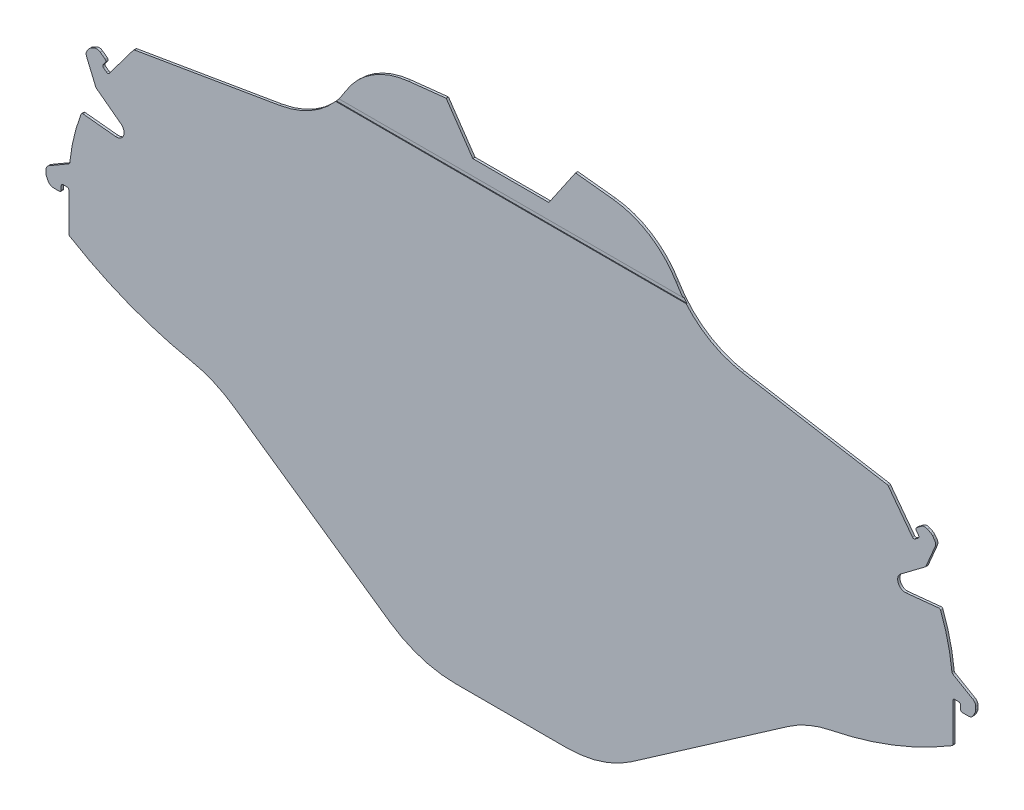
SolidWorks part; units mm, degrees
ref_plane "Front Plane" through (0, 0, 0) normal (0, 0, 1) x (1, 0, 0)
ref_plane "Top Plane" through (0, 0, 0) normal (0, 1, 0) x (1, 0, 0)
ref_plane "Right Plane" through (0, 0, 0) normal (1, 0, 0) x (0, 0, -1)
sketch "Sketch1" plane through (0, 0, 0) normal (0, 0, 1) x (1, 0, 0)
  line L0 (-24, -91.7648) -> (24, -91.7648)
  line L1 (0, 0) -> (0, -91.7648) construction
  line L2 (-10, 0) -> (-17, 10.2352)
  line L5 (-100.1804, -19.9556) -> (-60.7439, -13.2648)
  line L7 (-24, -91.7648) -> (-78.2662, -84.0567)
  line L8 (-17, 10.2352) -> (-26.9419, 9.1584)
  line L13 (-122.5, -58.7648) -> (122.5, -58.7648) construction
  line L14 (-60.7439, -13.2648) -> (-60.7439, -58.7648) construction
  line L15 (-113.5977, -28.7648) -> (-113.5977, -58.7648) construction
  line L16 (-10, 0) -> (10, 0)
  line L17 (10, 0) -> (17, 10.2352)
  line L18 (113.5977, -28.7648) -> (113.5977, -58.7648) construction
  line L19 (60.7439, -13.2648) -> (60.7439, -58.7648) construction
  line L20 (17, 10.2352) -> (26.9419, 9.1584)
  line L21 (24, -91.7648) -> (78.2662, -84.0567)
  line L22 (100.1804, -19.9556) -> (60.7439, -13.2648)
  line L23 (-17, 10.2352) -> (17, 10.2352) construction
  line L24 (0, 10.2352) -> (0, 0) construction
  arc A0 (-26.9419, 9.1584) -> (-43.4614, -1.4344) centre (-24.5729, -12.7137) ccw
  arc A1 (-43.4614, -1.4344) -> (-60.7439, -13.2648) centre (-64.9257, 11.383) cw
  arc A2 (-113.5977, -28.7648) -> (-100.1804, -19.9556) centre (-96.8349, -39.6739) cw
  arc A3 (-122.5, -58.7648) -> (-113.5977, -28.7648) centre (-67.5, -58.7648) cw
  arc A8 (-122.5, -58.7648) -> (-115.7111, -70.7648) centre (-108.5, -58.7648) ccw
  arc A9 (-115.7111, -70.7648) -> (-78.2662, -84.0567) centre (-64.2032, 14.9495) ccw
  arc A10 (115.7111, -70.7648) -> (78.2662, -84.0567) centre (64.2032, 14.9495) cw
  arc A11 (122.5, -58.7648) -> (115.7111, -70.7648) centre (108.5, -58.7648) cw
  arc A12 (122.5, -58.7648) -> (113.5977, -28.7648) centre (67.5, -58.7648) ccw
  arc A13 (113.5977, -28.7648) -> (100.1804, -19.9556) centre (96.8349, -39.6739) ccw
  arc A14 (43.4614, -1.4344) -> (60.7439, -13.2648) centre (64.9257, 11.383) ccw
  arc A15 (26.9419, 9.1584) -> (43.4614, -1.4344) centre (24.5729, -12.7137) cw
  dimension "D5" = 55
  dimension "D7" = 20
  dimension "D9" = 25
  dimension "D11" = 22
  dimension "D12" = 14
  dimension "D19" = 100
  dimension "D2" = 50.7439
  dimension "D3" = 102
  dimension "D4" = 10
  dimension "D6" = 14
  dimension "D8" = 40
  dimension "D10" = 58.7648
  dimension "D13" = 188.084
  dimension "D14" = 12.4
  dimension "D15" = 45.5
  dimension "D16" = 30
  dimension "D17" = 33
  dimension "D18" = 118.187
  dimension "D20" = 20
extrude "Main Shape" add sketch "Sketch1" along normal blind 0.6
sketch "Sketch2" plane through (0, 0, 0.6) normal (0, 0, 1) x (1, 0, 0)
  line L0 (0, 0) -> (0, -91.7648) construction
  line L1 (-24, -91.7648) -> (24, -91.7648) construction
  line L5 (-121.15, -59.7648) -> (-121.15, -57.7648)
  line L15 (-116.15, -59.7648) -> (-116.15, -70.4898)
  line L23 (118.15, -59.7648) -> (121.15, -59.7648) construction
  line L24 (113.6534, -43.3803) -> (119.6776, -41.3722) construction
  line L42 (-60.7439, -13.2648) -> (-100.1804, -19.9556) construction
  line L43 (-99.0635, -19.7662) -> (-100.1804, -19.9556)
  line L45 (-118.15, -59.7648) -> (-118.15, -61.7648)
  line L46 (-118.15, -61.7648) -> (-120.15, -61.7648)
  line L47 (-120.15, -61.7648) -> (-121.15, -59.7648)
  line L48 (-121.15, -57.7648) -> (-115.9855, -54.7675)
  line L49 (-113.6534, -43.3803) -> (-119.6776, -41.3722) construction
  line L50 (-111.02, -27.3748) -> (-108.6868, -32.8713)
  line L71 (-118.15, -59.7648) -> (-116.15, -59.7648)
  line L72 (-118.15, -59.7648) -> (-121.15, -59.7648) construction
  line L73 (-109.82, -25.7748) -> (-111.02, -27.3748)
  line L74 (-107.82, -24.7748) -> (-109.82, -25.7748)
  line L75 (-106.22, -25.9748) -> (-107.82, -24.7748)
  line L76 (-107.42, -27.5748) -> (-106.22, -25.9748)
  line L77 (-107.42, -27.5748) -> (-105.82, -28.7748)
  line L78 (-105.82, -28.7748) -> (-99.0635, -19.7662)
  line L79 (105.82, -28.7748) -> (99.0635, -19.7662)
  line L80 (107.42, -27.5748) -> (105.82, -28.7748)
  line L81 (107.42, -27.5748) -> (106.22, -25.9748)
  line L82 (106.22, -25.9748) -> (107.82, -24.7748)
  line L83 (107.82, -24.7748) -> (109.82, -25.7748)
  line L84 (109.82, -25.7748) -> (111.02, -27.3748)
  line L85 (118.15, -59.7648) -> (116.15, -59.7648)
  line L86 (111.02, -27.3748) -> (108.6868, -32.8713)
  line L87 (121.15, -57.7648) -> (115.9855, -54.7675)
  line L88 (120.15, -61.7648) -> (121.15, -59.7648)
  line L89 (118.15, -61.7648) -> (120.15, -61.7648)
  line L90 (118.15, -59.7648) -> (118.15, -61.7648)
  line L91 (99.0635, -19.7662) -> (100.1804, -19.9556)
  line L92 (116.15, -59.7648) -> (116.15, -70.4898)
  line L93 (121.15, -59.7648) -> (121.15, -57.7648)
  arc A9 (-106.42, -29.5748) -> (-116.15, -58.7648) centre (-67.5, -58.7648) ccw construction
  arc A11 (-113.5977, -28.7648) -> (-122.5, -58.7648) centre (-67.5, -58.7648) ccw construction
  arc A13 (-107.5, -28.7648) -> (-117.5, -58.7648) centre (-67.5, -58.7648) ccw construction
  arc A14 (-105.34, -30.3848) -> (-114.8, -58.7648) centre (-67.5, -58.7648) ccw construction
  arc A15 (-105.34, -30.3848) -> (-107.5, -28.7648) centre (-106.42, -29.5748) ccw construction
  arc A16 (-117.5, -58.7648) -> (-114.8, -58.7648) centre (-116.15, -58.7648) ccw construction
  arc A18 (115.9855, -54.7675) -> (108.6868, -32.8713) centre (67.5, -58.7648) ccw
  arc A19 (122.5, -58.7648) -> (116.15, -70.4898) centre (108.5, -58.7648) cw
  arc A21 (113.5977, -28.7648) -> (122.5, -58.7648) centre (67.5, -58.7648) cw
  arc A22 (100.1804, -19.9556) -> (113.5977, -28.7648) centre (96.8349, -39.6739) cw
  arc A23 (106.42, -29.5748) -> (116.15, -58.7648) centre (67.5, -58.7648) cw construction
  arc A33 (-122.5, -58.7648) -> (-115.7111, -70.7648) centre (-108.5, -58.7648) ccw construction
  arc A34 (-100.1804, -19.9556) -> (-113.5977, -28.7648) centre (-96.8349, -39.6739) ccw construction
  arc A35 (-100.1804, -19.9556) -> (-113.5977, -28.7648) centre (-96.8349, -39.6739) ccw
  arc A36 (-113.5977, -28.7648) -> (-122.5, -58.7648) centre (-67.5, -58.7648) ccw
  arc A37 (-122.5, -58.7648) -> (-116.15, -70.4898) centre (-108.5, -58.7648) ccw
  arc A39 (-115.9855, -54.7675) -> (-108.6868, -32.8713) centre (-67.5, -58.7648) cw
  arc A40 (107.5, -28.7648) -> (117.5, -58.7648) centre (67.5, -58.7648) cw construction
  arc A41 (105.34, -30.3848) -> (114.8, -58.7648) centre (67.5, -58.7648) cw construction
  arc A42 (105.34, -30.3848) -> (107.5, -28.7648) centre (106.42, -29.5748) cw construction
  arc A43 (117.5, -58.7648) -> (114.8, -58.7648) centre (116.15, -58.7648) cw construction
  point P24 (-113.6534, -43.3803)
  point P67 (113.6534, -43.3803)
  dimension "D1" = 1.35
  dimension "D2" = 5
  dimension "D3" = 2
  dimension "D7" = 1
  dimension "D4" = 2
  dimension "D5" = 2
  dimension "D6" = 2
  dimension "D8" = 5
  dimension "D9" = 3
extrude "Tabs" cut sketch "Sketch2" against normal through all both and the other way through all
sketch "Sketch5" plane through (0, 0, 0.6) normal (0, 0, 1) x (1, 0, 0)
  line L0 (-78.2662, -84.0567) -> (-24, -121.7648)
  line L1 (-24, -121.7648) -> (24, -121.7648)
  line L2 (24, -121.7648) -> (78.2662, -84.0567)
  line L3 (-78.2662, -84.0567) -> (-24, -91.7648) construction
  line L4 (24, -91.7648) -> (78.2662, -84.0567) construction
  line L5 (-24, -91.7648) -> (24, -91.7648) construction
  line L6 (24, -91.7648) -> (78.2662, -84.0567)
  line L7 (-24, -91.7648) -> (24, -91.7648)
  line L8 (-78.2662, -84.0567) -> (-24, -91.7648)
  dimension "D1" = 30
extrude "Chin guard" add sketch "Sketch5" against normal up to surface (0.6 mm away) up to face at (0, -39.2508, 0)
fillet "Fillet1" radius 30 4 edges at (-78.2662, -84.0567, 0.3) (78.2662, -84.0567, 0.3) (24, -121.7648, 0.3) (-24, -121.7648, 0.3)
sketch "Sketch8" plane through (0, 0, 0.6) normal (0, 0, 1) x (1, 0, 0)
  line L0 (10, 0) -> (-10, 0) construction
  line L1 (-50, -4) -> (50, -4)
  line L2 (-50, -4) -> (-50, -5)
  line L3 (-50, -5) -> (50, -5)
  line L4 (50, -4) -> (50, -5)
  point P5 (0, -4)
  dimension "D1" = 4
  dimension "D2" = 1
  dimension "D3" = 100
extrude "Cut-Extrude3" cut sketch "Sketch8" against normal blind 0.2
sketch "Sketch9" plane through (0, 0, 0.6) normal (0, 0, 1) x (1, 0, 0)
  line L1 (-113.6534, -43.3803) -> (-121.2429, -40.8505) construction
  line L2 (-121.15, -61.7648) -> (-120.15, -61.7648)
  line L3 (-121.15, -61.7648) -> (-122.15, -59.7648)
  line L4 (-122.15, -59.7648) -> (-122.15, -57.7648)
  line L5 (-121.15, -57.7648) -> (-121.15, -59.7648) construction
  line L6 (-121.15, -59.7648) -> (-120.15, -61.7648) construction
  line L7 (-122.15, -57.7648) -> (-115.9312, -54.1556)
  line L8 (-115.9855, -54.7675) -> (-121.15, -57.7648) construction
  line L9 (-120.15, -61.7648) -> (-121.15, -59.7648)
  line L10 (-121.15, -59.7648) -> (-121.15, -57.7648)
  line L11 (-121.15, -57.7648) -> (-115.9855, -54.7675)
  line L12 (-111.02, -27.3748) -> (-108.6868, -32.8713)
  line L14 (-109.82, -25.7748) -> (-111.02, -27.3748)
  line L15 (-107.82, -24.7748) -> (-109.82, -25.7748)
  line L16 (-111.82, -26.7748) -> (-109.0104, -33.3934)
  line L17 (-110.62, -25.1748) -> (-111.82, -26.7748)
  line L18 (-108.62, -24.1748) -> (-110.62, -25.1748)
  line L19 (-108.62, -24.1748) -> (-107.82, -24.7748)
  line L20 (0, -0.33) -> (0, 0.33) construction
  line L21 (113.6534, -43.3803) -> (121.2429, -40.8505) construction
  line L22 (108.62, -24.1748) -> (107.82, -24.7748)
  line L23 (108.62, -24.1748) -> (110.62, -25.1748)
  line L24 (110.62, -25.1748) -> (111.82, -26.7748)
  line L25 (111.82, -26.7748) -> (109.0104, -33.3934)
  line L26 (107.82, -24.7748) -> (109.82, -25.7748)
  line L27 (109.82, -25.7748) -> (111.02, -27.3748)
  line L28 (111.02, -27.3748) -> (108.6868, -32.8713)
  line L29 (121.15, -57.7648) -> (115.9855, -54.7675)
  line L30 (121.15, -59.7648) -> (121.15, -57.7648)
  line L31 (120.15, -61.7648) -> (121.15, -59.7648)
  line L32 (122.15, -57.7648) -> (115.9312, -54.1556)
  line L33 (122.15, -59.7648) -> (122.15, -57.7648)
  line L34 (121.15, -61.7648) -> (122.15, -59.7648)
  line L35 (121.15, -61.7648) -> (120.15, -61.7648)
  arc A0 (-108.6868, -32.8713) -> (-115.9855, -54.7675) centre (-67.5, -58.7648) ccw construction
  arc A2 (115.9855, -54.7675) -> (108.6868, -32.8713) centre (67.5, -58.7648) ccw construction
  arc A4 (-108.6868, -32.8713) -> (-115.9855, -54.7675) centre (-67.5, -58.7648) ccw construction
  arc A5 (109.0104, -33.3934) -> (108.6868, -32.8713) centre (67.5, -58.7648) ccw
  arc A6 (-115.9312, -54.1556) -> (-115.9855, -54.7675) centre (-67.5, -58.7648) ccw
  arc A7 (-115.9855, -54.7675) -> (-108.6868, -32.8713) centre (-67.5, -58.7648) cw construction
  arc A8 (-109.0104, -33.3934) -> (-108.6868, -32.8713) centre (-67.5, -58.7648) cw
  arc A9 (115.9312, -54.1556) -> (115.9855, -54.7675) centre (67.5, -58.7648) cw
  dimension "D1" = 1
  dimension "D2" = 8
extrude "Boss-Extrude1" add sketch "Sketch9" against normal up to surface (0.6 mm away) up to face at (0, -45.2113, 0)
sketch "Sketch7" plane through (0, 0, 0.6) normal (0, 0, 1) x (1, 0, 0)
  line L3 (-103.8386, -41.9134) -> (-112.7927, -41.0055)
  line L6 (-109.0104, -33.3934) -> (-102.4369, -38.3236)
  line L7 (-105.82, -28.7748) -> (-107.42, -27.5748) construction
  line L8 (0, -0.33) -> (0, 0.33) construction
  line L9 (109.0104, -33.3934) -> (102.4369, -38.3236)
  line L10 (103.8386, -41.9134) -> (112.7927, -41.0055)
  arc A1 (-103.8386, -41.9134) -> (-102.4369, -38.3236) centre (-103.6369, -39.9236) ccw
  arc A5 (-109.0104, -33.3934) -> (-115.9312, -54.1556) centre (-67.5, -58.7648) ccw construction
  arc A6 (-109.0104, -33.3934) -> (-112.7927, -41.0055) centre (-67.5, -58.7648) ccw
  arc A7 (109.0104, -33.3934) -> (112.7927, -41.0055) centre (67.5, -58.7648) cw
  arc A8 (103.8386, -41.9134) -> (102.4369, -38.3236) centre (103.6369, -39.9236) cw
  dimension "D2" = 2
  dimension "D1" = 8.5
  dimension "D3" = 9
extrude "Cut-Extrude4" cut sketch "Sketch7" against normal through all both and the other way through all
fillet "Fillet2" radius 0.5 22 edges at (109.0104, -33.3934, 0.3) (-112.7927, -41.0055, 0.3) (-109.0104, -33.3934, 0.3) (-106.22, -25.9748, 0.3) (-107.42, -27.5748, 0.3) (-105.82, -28.7748, 0.3) (-115.9312, -54.1556, 0.3) (-118.15, -61.7648, 0.3) (-116.15, -59.7648, 0.3) (-118.15, -59.7648, 0.3) (118.15, -61.7648, 0.3) (118.15, -59.7648, 0.3) (116.15, -59.7648, 0.3) (105.82, -28.7748, 0.3) (107.42, -27.5748, 0.3) (106.22, -25.9748, 0.3) (115.9312, -54.1556, 0.3) (112.7927, -41.0055, 0.3) (99.0635, -19.7662, 0.3) (-99.0635, -19.7662, 0.3)
fillet "Fillet3" radius 1.5 12 edges at (121.15, -61.7648, 0.3) (122.15, -59.7648, 0.3) (122.15, -57.7648, 0.3) (108.62, -24.1748, 0.3) (110.62, -25.1748, 0.3) (111.82, -26.7748, 0.3) (-108.62, -24.1748, 0.3) (-110.62, -25.1748, 0.3) (-111.82, -26.7748, 0.3) (-122.15, -57.7648, 0.3) (-122.15, -59.7648, 0.3) (-121.15, -61.7648, 0.3)
